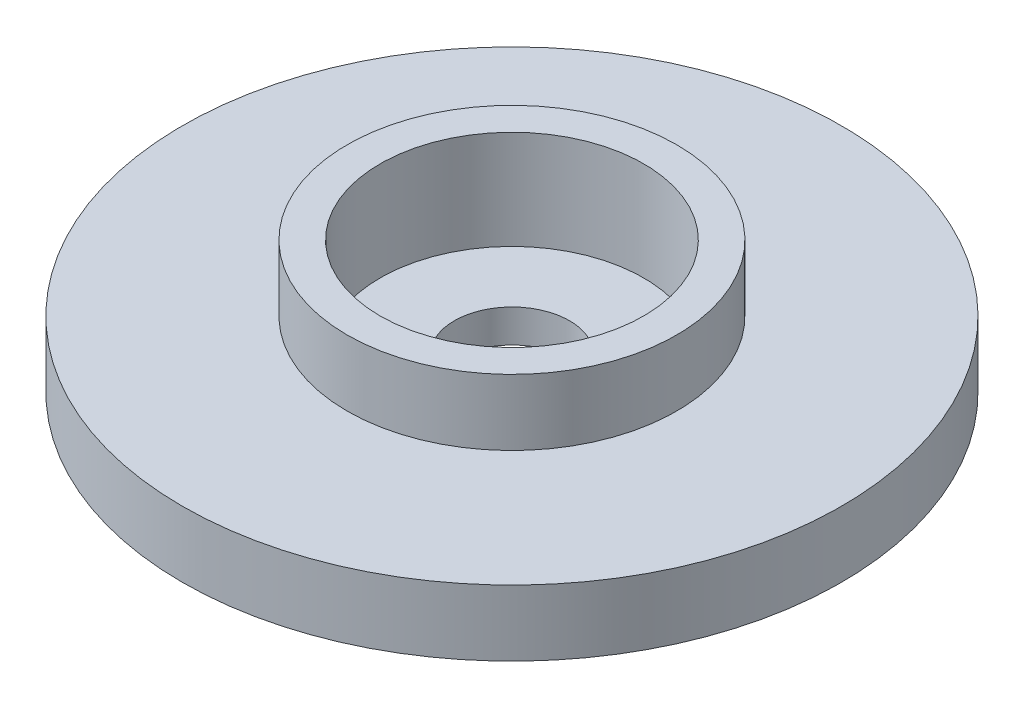
SolidWorks part; units mm, degrees
ref_plane "前视基准面" through (0, 0, 0) normal (0, 0, 1) x (1, 0, 0)
ref_plane "上视基准面" through (0, 0, 0) normal (0, 1, 0) x (1, 0, 0)
ref_plane "右视基准面" through (0, 0, 0) normal (1, 0, 0) x (0, 0, -1)
sketch "草图1" plane through (0, 0, 0) normal (0, 1, 0) x (1, 0, 0)
  circle A0 centre (0, 0) radius 10
  dimension "D2" = 20
extrude "凸台-拉伸1" add sketch "草图1" along normal blind 2
sketch "草图2" plane through (0, 2, 0) normal (0, 1, 0) x (1, 0, 0)
  circle A0 centre (0, 0) radius 5
  dimension "D1" = 10
extrude "凸台-拉伸2" add sketch "草图2" along normal blind 2
sketch "草图3" plane through (0, 4, 0) normal (0, 1, 0) x (1, 0, 0)
  circle A0 centre (0, 0) radius 1.75
  dimension "D1" = 3.5
extrude "切除-拉伸1" cut sketch "草图3" against normal through all
sketch "草图4" plane through (0, 4, 0) normal (0, 1, 0) x (1, 0, 0)
  circle A0 centre (0, 0) radius 4
  dimension "D1" = 8
extrude "切除-拉伸2" cut sketch "草图4" against normal blind 3
